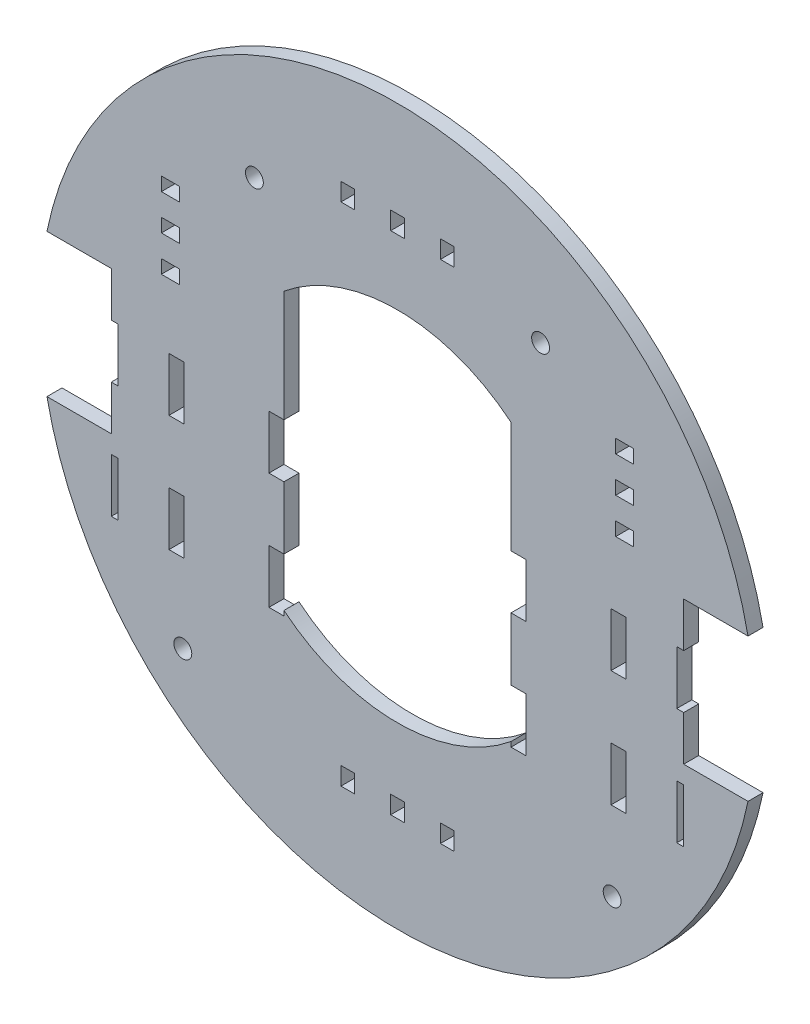
SolidWorks part; units mm, degrees
ref_plane "Front Plane" through (0, 0, 0) normal (0, 0, 1) x (1, 0, 0)
ref_plane "Top Plane" through (0, 0, 0) normal (0, 1, 0) x (1, 0, 0)
ref_plane "Right Plane" through (0, 0, 0) normal (1, 0, 0) x (0, 0, -1)
sketch "Sketch1" plane through (0, 0, 0) normal (0, 0, 1) x (1, 0, 0)
  line L2 (-40.3, 49.073) -> (-40.3, -49.073)
  line L4 (40.3, 49.073) -> (40.3, -49.073)
  circle A0 centre (0, 0) radius 127
  circle A1 centre (0, 0) radius 63.5
  dimension "D1" = 254
  dimension "D2" = 127
  dimension "D3" = 40.3
extrude "Boss-Extrude1" add sketch "Sketch1" along normal blind 5.334 contours A0 A1 | L2 A1 | L4 A1
sketch "Sketch2" plane through (0, 0, 5.334) normal (0, 0, 1) x (1, 0, 0)
  line L0 (0, 0) -> (50000, 0) construction
  line L1 (0, 0) -> (0, 50000) construction
  line L2 (152.4, -25.4) -> (101.6, 25.4) construction
  line L3 (-152.4, 25.4) -> (-101.6, 25.4)
  line L4 (-152.4, 25.4) -> (-152.4, -25.4)
  line L5 (-152.4, -25.4) -> (-101.6, -25.4)
  line L6 (-101.6, 25.4) -> (-101.6, -25.4)
  line L7 (-152.4, 25.4) -> (-101.6, -25.4) construction
  line L8 (-152.4, -25.4) -> (-101.6, 25.4) construction
  line L9 (152.4, 25.4) -> (101.6, -25.4) construction
  line L10 (101.6, 25.4) -> (101.6, -25.4)
  line L11 (152.4, -25.4) -> (101.6, -25.4)
  line L12 (152.4, 25.4) -> (152.4, -25.4)
  line L13 (152.4, 25.4) -> (101.6, 25.4)
  circle A0 centre (0, 0) radius 127 construction
  point P5 (-127, 0)
  point P16 (127, 0)
  dimension "D1" = 50.8
  dimension "D2" = 101.6
extrude "WheelsCut" cut sketch "Sketch2" against normal through all
sketch "Sketch3" plane through (0, 0, 5.334) normal (0, 0, 1) x (1, 0, 0)
  line L0 (0, 0) -> (0, 50000) construction
  line L1 (-20.066, 92.964) -> (-15.24, 92.964)
  line L2 (-20.066, 92.964) -> (-20.066, 86.614)
  line L3 (-20.066, 86.614) -> (-15.24, 86.614)
  line L4 (-15.24, 92.964) -> (-15.24, 86.614)
  line L5 (0, 0) -> (50000, 0) construction
  line L6 (15.24, 92.964) -> (15.24, 86.614)
  line L7 (2.413, -86.614) -> (-2.413, -86.614)
  line L8 (2.413, 92.964) -> (-2.413, 92.964)
  line L9 (2.413, 92.964) -> (2.413, 86.614)
  line L10 (2.413, 86.614) -> (-2.413, 86.614)
  line L11 (-2.413, 92.964) -> (-2.413, 86.614)
  line L12 (2.413, 92.964) -> (-2.413, 86.614) construction
  line L13 (20.066, 86.614) -> (15.24, 86.614)
  line L14 (20.066, 92.964) -> (20.066, 86.614)
  line L15 (20.066, 92.964) -> (15.24, 92.964)
  line L16 (2.413, -92.964) -> (2.413, -86.614)
  line L17 (-2.413, -92.964) -> (-2.413, -86.614)
  line L18 (20.066, -92.964) -> (15.24, -92.964)
  line L19 (20.066, -92.964) -> (20.066, -86.614)
  line L20 (20.066, -86.614) -> (15.24, -86.614)
  line L21 (2.413, -92.964) -> (-2.413, -92.964)
  line L25 (15.24, -92.964) -> (15.24, -86.614)
  line L26 (-15.24, -92.964) -> (-15.24, -86.614)
  line L27 (-20.066, -86.614) -> (-15.24, -86.614)
  line L28 (-20.066, -92.964) -> (-20.066, -86.614)
  line L29 (-20.066, -92.964) -> (-15.24, -92.964)
  line L30 (2.413, 86.614) -> (-2.413, 92.964) construction
  point P9 (0, 89.789)
  dimension "D1" = 86.614
  dimension "D2" = 4.826
  dimension "D3" = 15.24
  dimension "D4" = 4.826
  dimension "D5" = 6.35
extrude "TopBottomCut" cut sketch "Sketch3" against normal through all
sketch "Sketch4" plane through (0, 0, 5.334) normal (0, 0, 1) x (1, 0, 0)
  line L0 (0, 0) -> (0, 50000) construction
  line L1 (0, 0) -> (50000, 0) construction
  line L2 (-83.82, 45.212) -> (-77.47, 45.212)
  line L3 (-83.82, 32.512) -> (-77.47, 32.512)
  line L4 (-83.82, 32.512) -> (-83.82, 37.338)
  line L5 (-83.82, 37.338) -> (-77.47, 37.338)
  line L6 (-77.47, 32.512) -> (-77.47, 37.338)
  line L7 (-83.82, 45.212) -> (-83.82, 50.038)
  line L8 (-83.82, 50.038) -> (-77.47, 50.038)
  line L9 (-77.47, 45.212) -> (-77.47, 50.038)
  line L10 (-83.82, 57.912) -> (-77.47, 57.912)
  line L11 (-83.82, 57.912) -> (-83.82, 62.738)
  line L12 (-83.82, 62.738) -> (-77.47, 62.738)
  line L13 (-77.47, 57.912) -> (-77.47, 62.738)
  line L14 (77.47, 57.912) -> (77.47, 62.738)
  line L15 (83.82, 62.738) -> (77.47, 62.738)
  line L16 (83.82, 57.912) -> (83.82, 62.738)
  line L17 (83.82, 57.912) -> (77.47, 57.912)
  line L18 (77.47, 45.212) -> (77.47, 50.038)
  line L19 (83.82, 50.038) -> (77.47, 50.038)
  line L20 (83.82, 45.212) -> (83.82, 50.038)
  line L21 (77.47, 32.512) -> (77.47, 37.338)
  line L22 (83.82, 37.338) -> (77.47, 37.338)
  line L23 (83.82, 32.512) -> (83.82, 37.338)
  line L24 (83.82, 32.512) -> (77.47, 32.512)
  line L25 (83.82, 45.212) -> (77.47, 45.212)
  dimension "D1" = 77.47
  dimension "D2" = 4.826
  dimension "D3" = 6.35
  dimension "D5" = 32.512
  dimension "D6" = 7.874
  dimension "D4" = 3
extrude "SideCut" cut sketch "Sketch4" against normal through all
sketch "Sketch14" plane through (0, 0, 5.334) normal (0, 0, 1) x (1, 0, 0)
  line L0 (0, 0) -> (50000, 0) construction
  line L1 (0, 0) -> (0, 50000) construction
  circle A0 centre (-76.2, -78.74) radius 3.175
  circle A1 centre (-50.8, 78.74) radius 3.175
  circle A2 centre (76.2, -78.74) radius 3.175
  circle A3 centre (50.8, 78.74) radius 3.175
  dimension "D1" = 6.35
  dimension "D2" = 6.35
  dimension "D3" = 50.8
  dimension "D4" = 78.74
  dimension "D5" = 78.74
  dimension "D6" = 76.2
extrude "BoltHoles" cut sketch "Sketch14" against normal through all
sketch "Sketch15" plane through (0, 0, 5.334) normal (0, 0, 1) x (1, 0, 0)
  line L0 (0, 0) -> (-50000, 0) construction
  line L1 (-101.6, -31.75) -> (-99.1362, -31.75)
  line L2 (-101.6, 9.525) -> (-99.1362, 9.525)
  line L3 (-101.6, 9.525) -> (-101.6, -9.525)
  line L4 (-101.6, -9.525) -> (-99.1362, -9.525)
  line L5 (0, 0) -> (0, 50000) construction
  line L6 (-99.1362, 9.525) -> (-99.1362, -9.525)
  line L7 (-101.6, 9.525) -> (-99.1362, -9.525) construction
  line L8 (-101.6, -9.525) -> (-99.1362, 9.525) construction
  line L9 (-81.1362, 9.525) -> (-75.8022, 9.525)
  line L10 (-81.1362, 9.525) -> (-81.1362, -9.525)
  line L11 (-81.1362, -9.525) -> (-75.8022, -9.525)
  line L12 (-75.8022, 9.525) -> (-75.8022, -9.525)
  line L13 (-81.1362, 9.525) -> (-75.8022, -9.525) construction
  line L14 (-81.1362, -9.525) -> (-75.8022, 9.525) construction
  line L15 (-45.634, -9.525) -> (-40.3, -9.525)
  line L16 (-45.634, -9.525) -> (-45.634, 9.525)
  line L17 (-45.634, 9.525) -> (-40.3, 9.525)
  line L18 (-40.3, -9.525) -> (-40.3, 9.525)
  line L19 (-45.634, -9.525) -> (-40.3, 9.525) construction
  line L20 (-45.634, 9.525) -> (-40.3, -9.525) construction
  line L21 (-101.6, -31.75) -> (-101.6, -50.8)
  line L22 (-101.6, -50.8) -> (-99.1362, -50.8)
  line L23 (-99.1362, -31.75) -> (-99.1362, -50.8)
  line L24 (-81.1362, -31.75) -> (-75.8022, -31.75)
  line L25 (-81.1362, -31.75) -> (-81.1362, -50.8)
  line L26 (-81.1362, -50.8) -> (-75.8022, -50.8)
  line L27 (-75.8022, -31.75) -> (-75.8022, -50.8)
  line L28 (-45.634, -50.8) -> (-40.3, -50.8)
  line L29 (-45.634, -50.8) -> (-45.634, -31.75)
  line L30 (-45.634, -31.75) -> (-40.3, -31.75)
  line L31 (-40.3, -50.8) -> (-40.3, -31.75)
  line L32 (-101.6, -31.75) -> (-99.1362, -50.8) construction
  line L33 (-101.6, -50.8) -> (-99.1362, -31.75) construction
  line L34 (-81.1362, -31.75) -> (-75.8022, -50.8) construction
  line L35 (-81.1362, -50.8) -> (-75.8022, -31.75) construction
  line L36 (-45.634, -50.8) -> (-40.3, -31.75) construction
  line L37 (-45.634, -31.75) -> (-40.3, -50.8) construction
  line L38 (45.634, -31.75) -> (40.3, -50.8) construction
  line L39 (45.634, -50.8) -> (40.3, -31.75) construction
  line L40 (81.1362, -50.8) -> (75.8022, -31.75) construction
  line L41 (81.1362, -31.75) -> (75.8022, -50.8) construction
  line L42 (101.6, -50.8) -> (99.1362, -31.75) construction
  line L43 (101.6, -31.75) -> (99.1362, -50.8) construction
  line L44 (45.634, 9.525) -> (40.3, -9.525) construction
  line L45 (45.634, -9.525) -> (40.3, 9.525) construction
  line L46 (81.1362, -9.525) -> (75.8022, 9.525) construction
  line L47 (81.1362, 9.525) -> (75.8022, -9.525) construction
  line L48 (101.6, -9.525) -> (99.1362, 9.525) construction
  line L49 (101.6, 9.525) -> (99.1362, -9.525) construction
  line L50 (40.3, -50.8) -> (40.3, -31.75)
  line L51 (45.634, -31.75) -> (40.3, -31.75)
  line L52 (45.634, -50.8) -> (45.634, -31.75)
  line L53 (45.634, -50.8) -> (40.3, -50.8)
  line L54 (75.8022, -31.75) -> (75.8022, -50.8)
  line L55 (-122.4001, 9.525) -> (-24.2402, 9.525) construction
  line L56 (81.1362, -50.8) -> (75.8022, -50.8)
  line L57 (81.1362, -31.75) -> (81.1362, -50.8)
  line L58 (81.1362, -31.75) -> (75.8022, -31.75)
  line L59 (99.1362, -31.75) -> (99.1362, -50.8)
  line L60 (101.6, -50.8) -> (99.1362, -50.8)
  line L61 (101.6, -31.75) -> (101.6, -50.8)
  line L62 (40.3, -9.525) -> (40.3, 9.525)
  line L63 (45.634, 9.525) -> (40.3, 9.525)
  line L64 (45.634, -9.525) -> (45.634, 9.525)
  line L65 (45.634, -9.525) -> (40.3, -9.525)
  line L66 (75.8022, 9.525) -> (75.8022, -9.525)
  line L67 (81.1362, -9.525) -> (75.8022, -9.525)
  line L68 (81.1362, 9.525) -> (81.1362, -9.525)
  line L69 (81.1362, 9.525) -> (75.8022, 9.525)
  line L70 (99.1362, 9.525) -> (99.1362, -9.525)
  line L71 (101.6, -9.525) -> (99.1362, -9.525)
  line L72 (101.6, 9.525) -> (101.6, -9.525)
  line L73 (101.6, 9.525) -> (99.1362, 9.525)
  line L74 (101.6, -31.75) -> (99.1362, -31.75)
  point P0 (-100.3681, 0)
  point P10 (-78.4692, 0)
  point P15 (-42.967, 0)
  point P21 (-100.3681, -41.275)
  point P28 (-78.4692, -41.275)
  point P33 (-42.967, -41.275)
  point P61 (42.967, -41.275)
  point P62 (78.4692, -41.275)
  point P63 (100.3681, -41.275)
  point P64 (42.967, 0)
  point P65 (78.4692, 0)
  point P66 (100.3681, 0)
  dimension "D1" = 19.05
  dimension "D2" = 99.1362
  dimension "D3" = 2.4638
  dimension "D5" = 40.3
  dimension "D6" = 75.8022
  dimension "D7" = 2
  dimension "D8" = 22.225
  dimension "D10" = 22.225
  dimension "D11" = 5.334
  dimension "D4" = 5.334
  dimension "D9" = 22.225
extrude "MotorMounts" cut sketch "Sketch15" against normal through all
